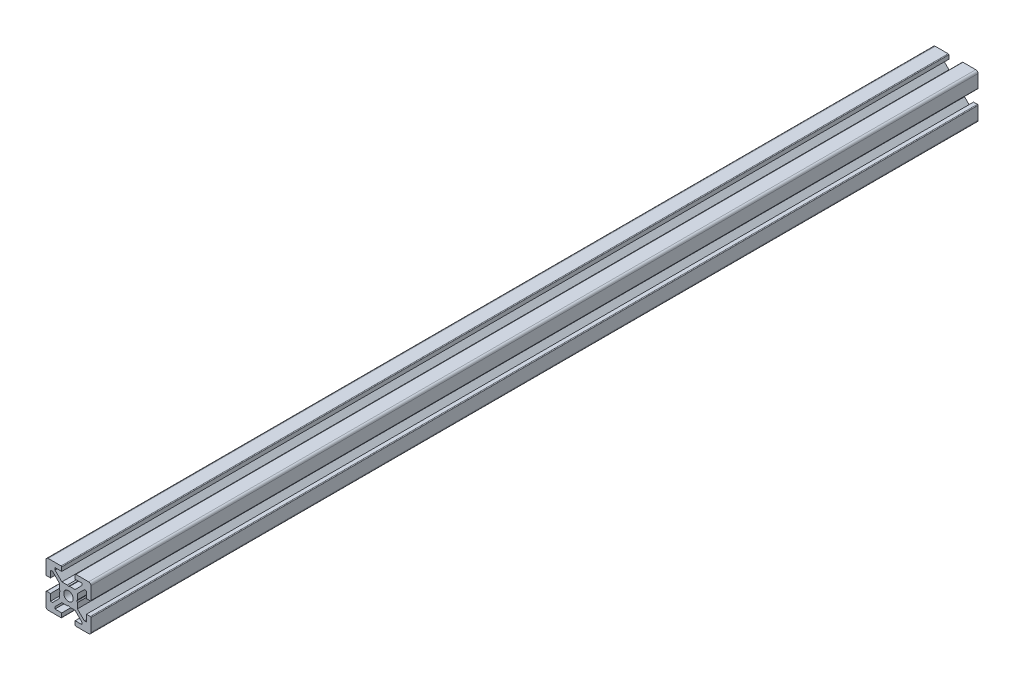
SolidWorks part; units mm, degrees
ref_plane "Front Plane" through (0, 0, 0) normal (0, 0, 1) x (1, 0, 0)
ref_plane "Top Plane" through (0, 0, 0) normal (0, 1, 0) x (1, 0, 0)
ref_plane "Right Plane" through (0, 0, 0) normal (1, 0, 0) x (0, 0, -1)
ref_plane "Plane1" through (0, 0, 0) normal (0, 0, 1) x (1, 0, 0)
sketch "Sketch1" plane through (0, 0, 0) normal (0, 0, 1) x (1, 0, 0)
  line L0 (-10, 9) -> (-10, 3.3)
  line L1 (-9.7, 3) -> (-8, 3)
  line L2 (-8, 3) -> (-8, 6)
  line L3 (-8, 6) -> (-7.0607, 6)
  line L4 (-7.0607, 6) -> (-4, 2.9393)
  line L5 (-4, 2.9393) -> (-4, 0.5196)
  line L6 (-4, 0.5196) -> (-3.7, 0)
  line L7 (-3.7, 0) -> (-4, -0.5196)
  line L8 (-4, -0.5196) -> (-4, -2.9393)
  line L9 (-4, -2.9393) -> (-7.0607, -6)
  line L10 (-7.0607, -6) -> (-8, -6)
  line L11 (-8, -6) -> (-8, -3)
  line L12 (-8, -3) -> (-9.7, -3)
  line L13 (-10, -3.3) -> (-10, -9)
  line L14 (-9, -10) -> (-3.3, -10)
  line L15 (-3, -9.7) -> (-3, -8)
  line L16 (-3, -8) -> (-6, -8)
  line L17 (-6, -8) -> (-6, -7.0607)
  line L18 (-6, -7.0607) -> (-2.9393, -4)
  line L19 (-2.9393, -4) -> (-0.5196, -4)
  line L20 (-0.5196, -4) -> (0, -3.7)
  line L21 (0, -3.7) -> (0.5196, -4)
  line L22 (0.5196, -4) -> (2.9393, -4)
  line L23 (2.9393, -4) -> (6, -7.0607)
  line L24 (6, -7.0607) -> (6, -8)
  line L25 (6, -8) -> (3, -8)
  line L26 (3, -8) -> (3, -9.7)
  line L27 (3.3, -10) -> (9, -10)
  line L28 (10, -9) -> (10, -3.3)
  line L29 (9.7, -3) -> (8, -3)
  line L30 (8, -3) -> (8, -6)
  line L31 (8, -6) -> (7.0606, -6)
  line L32 (7.0606, -6) -> (4, -2.9393)
  line L33 (4, -2.9393) -> (4, -0.5196)
  line L34 (4, -0.5196) -> (3.7, 0)
  line L35 (3.7, 0) -> (4, 0.5196)
  line L36 (4, 0.5196) -> (4, 2.9393)
  line L37 (4, 2.9393) -> (7.0607, 6)
  line L38 (7.0607, 6) -> (8, 6)
  line L39 (8, 6) -> (8, 3)
  line L40 (8, 3) -> (9.7, 3)
  line L41 (10, 3.3) -> (10, 9)
  line L42 (9, 10) -> (3.3, 10)
  line L43 (3, 9.7) -> (3, 8)
  line L44 (3, 8) -> (6, 8)
  line L45 (6, 8) -> (6, 7.0607)
  line L46 (6, 7.0607) -> (2.9393, 4)
  line L47 (2.9393, 4) -> (0.5196, 4)
  line L48 (0.5196, 4) -> (0, 3.7)
  line L49 (0, 3.7) -> (-0.5196, 4)
  line L50 (-0.5196, 4) -> (-2.9394, 4)
  line L51 (-2.9394, 4) -> (-6, 7.0606)
  line L52 (-6, 7.0606) -> (-6, 8)
  line L53 (-6, 8) -> (-3, 8)
  line L54 (-3, 8) -> (-3, 9.7)
  line L55 (-3.3, 10) -> (-9, 10)
  arc A0 (-10, 3.3) -> (-9.7, 3) centre (-9.7, 3.3) ccw
  arc A1 (-9.7, -3) -> (-10, -3.3) centre (-9.7, -3.3) ccw
  arc A2 (-10, -9) -> (-9, -10) centre (-9, -9) ccw
  arc A3 (-3.3, -10) -> (-3, -9.7) centre (-3.3, -9.7) ccw
  arc A4 (3, -9.7) -> (3.3, -10) centre (3.3, -9.7) ccw
  arc A5 (9, -10) -> (10, -9) centre (9, -9) ccw
  arc A6 (10, -3.3) -> (9.7, -3) centre (9.7, -3.3) ccw
  arc A7 (9.7, 3) -> (10, 3.3) centre (9.7, 3.3) ccw
  arc A8 (10, 9) -> (9, 10) centre (9, 9) ccw
  arc A9 (3.3, 10) -> (3, 9.7) centre (3.3, 9.7) ccw
  arc A10 (-3, 9.7) -> (-3.3, 10) centre (-3.3, 9.7) ccw
  arc A11 (-9, 10) -> (-10, 9) centre (-9, 9) ccw
extrude "Boss-Extrude1" add sketch "Sketch1" against normal blind 395
ref_plane "Plane2" through (0, 0, 0) normal (1, 0, 0) x (0, 0, -1)
sketch "Sketch2" plane through (0, 0, 0) normal (1, 0, 0) x (0, 0, -1)
  line L0 (0, 0) -> (0, 2.1)
  line L1 (0, 2.1) -> (400, 2.1)
  line L2 (400, 2.1) -> (400, 0)
  line L3 (400, 0) -> (0, 0)
  line L4 (400, 0) -> (0, 0) construction
revolve "Cut-Revolve1" cut sketch "Sketch2" angle 360 about L4
